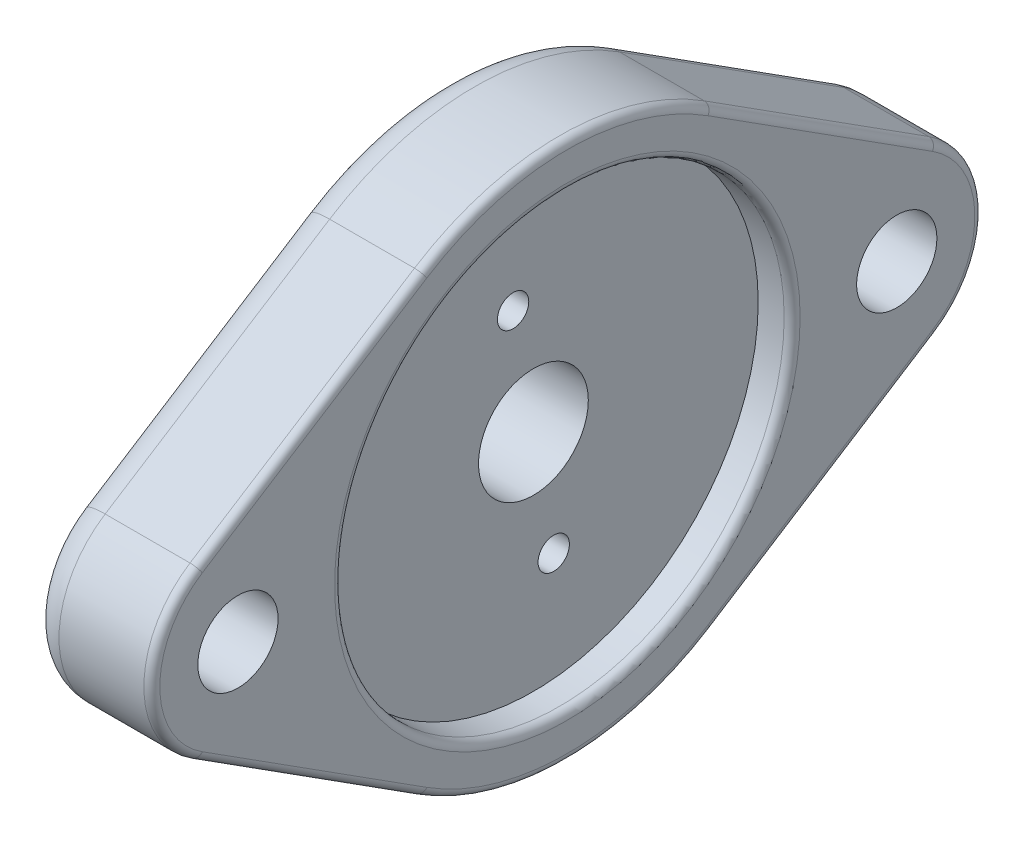
SolidWorks part; units mm, degrees
material "ABS"
ref_plane "Front Plane" through (0, 0, 0) normal (0, 0, 1) x (1, 0, 0)
ref_plane "Top Plane" through (0, 0, 0) normal (0, 1, 0) x (1, 0, 0)
ref_plane "Right Plane" through (0, 0, 0) normal (1, 0, 0) x (0, 0, -1)
sketch "Sketch1" plane through (0, 0, 0) normal (1, 0, 0) x (0, 0, -1)
  line L6 (9.2165, 14.4571) -> (23.495, 5.3545)
  line L9 (-9.2165, 14.4571) -> (-23.495, 5.3545)
  line L13 (-23.495, -5.3545) -> (-9.2165, -14.4571)
  line L14 (23.495, -5.3545) -> (9.2165, -14.4571)
  line L21 (23.495, 5.3545) -> (23.495, -5.3545) construction
  line L22 (-20.0815, 0) -> (20.0815, 0) construction
  line L23 (23.495, -5.3545) -> (-23.495, -5.3545) construction
  line L24 (-23.495, -5.3545) -> (-23.495, 5.3545) construction
  line L25 (23.495, 5.3545) -> (-23.495, 5.3545) construction
  arc A6 (23.495, 5.3545) -> (23.495, -5.3545) centre (20.0815, 0) cw
  arc A7 (-23.495, 5.3545) -> (-23.495, -5.3545) centre (-20.0815, 0) ccw
  arc A8 (-9.2165, -14.4571) -> (9.2165, -14.4571) centre (0, 0) ccw
  arc A9 (9.2165, 14.4571) -> (-9.2165, 14.4571) centre (0, 0) ccw
  dimension "D1" = 17.145
  dimension "D2" = 46.99
  dimension "D3" = 6.35
extrude "Boss-Extrude3" add sketch "Sketch1" along normal blind 7.9375
sketch "Sketch5" plane through (7.9375, 0, 0) normal (1, 0, 0) x (0, 0, -1)
  circle A0 centre (0, 0) radius 3.4925
  dimension "D1" = 6.985
extrude "Cut-Extrude4" cut sketch "Sketch5" against normal through all
sketch "Sketch6" plane through (7.9375, 0, 0) normal (1, 0, 0) x (0, 0, -1)
  circle A0 centre (0, 0) radius 14.3002
  dimension "D1" = 28.6004
extrude "Cut-Extrude5" cut sketch "Sketch6" against normal blind 2.159
hole_wizard "Tap Drill for #3-48 Tap2" positions "Sketch10" profile "Sketch11" hole size "#3-48" standard "ANSI Inch" end condition through all
sketch "Sketch10" plane through (5.7785, 0, 0) normal (1, 0, 0) x (0, 0, -1)
  line L0 (1.2923, -7.3291) -> (-1.2923, 7.3291) construction
  line L1 (0, 0) -> (0, 10.5936) construction
  point P0 (-1.2923, 7.3291)
  point P2 (1.2923, -7.3291)
  dimension "D1" = 14.8844
  dimension "D2" = 10
sketch "Sketch11" plane through (5.7785, 7.3291, 1.2923) normal (0, 1, 0) x (0, 0, -1)
  line L0 (0, 0) -> (0, 5.7785)
  line L1 (0, 5.7785) -> (0.9969, 5.7785)
  line L2 (0.9969, 5.7785) -> (0.9969, 0)
  line L5 (0.9969, 0) -> (0, 0)
  line L11 (0, -6.35) -> (0, 107.95) construction
  dimension "Thru Hole Dia." = 1.9939
  dimension "Thru Hole Depth" = 5.7785
hole_wizard "#10 Clearance Hole1" positions "Sketch16" profile "Sketch17" hole size "#10" standard "ANSI Inch" end condition through all
sketch "Sketch16" plane through (7.9375, 0, 0) normal (1, 0, 0) x (0, 0, -1)
  line L4 (-20.955, 0) -> (20.955, 0) construction
  point P0 (-20.955, 0)
  point P2 (20.955, 0)
  point P22 (9.9005, 18.6956)
  dimension "D1" = 41.91
sketch "Sketch17" plane through (7.9375, 0, 20.955) normal (0, 1, 0) x (0, 0, -1)
  line L0 (0, 0) -> (0, 7.9375)
  line L1 (0, 7.9375) -> (2.5527, 7.9375)
  line L2 (2.5527, 7.9375) -> (2.5527, 0)
  line L5 (2.5527, 0) -> (0, 0)
  line L11 (0, -6.35) -> (0, 107.95) construction
  dimension "Thru Hole Dia." = 5.1054
  dimension "Thru Hole Depth" = 7.9375
fillet "Fillet1" radius 2.032 8 edges at (0, 17.145, 0) (0, 9.9058, -16.3557) (0, 0, -26.4315) (0, -9.9058, -16.3557) (0, -17.145, 0) (0, -9.9058, 16.3557) (0, 0, 26.4315) (0, 9.9058, 16.3557)
fillet "Fillet2" radius 0.508 9 edges at (7.9375, 0, -14.3002) (7.9375, 0, -26.4315) (7.9375, -9.9058, -16.3557) (7.9375, -17.145, 0) (7.9375, -9.9058, 16.3557) (7.9375, 0, 26.4315) (7.9375, 9.9058, 16.3557) (7.9375, 17.145, 0) (7.9375, 9.9058, -16.3557)
